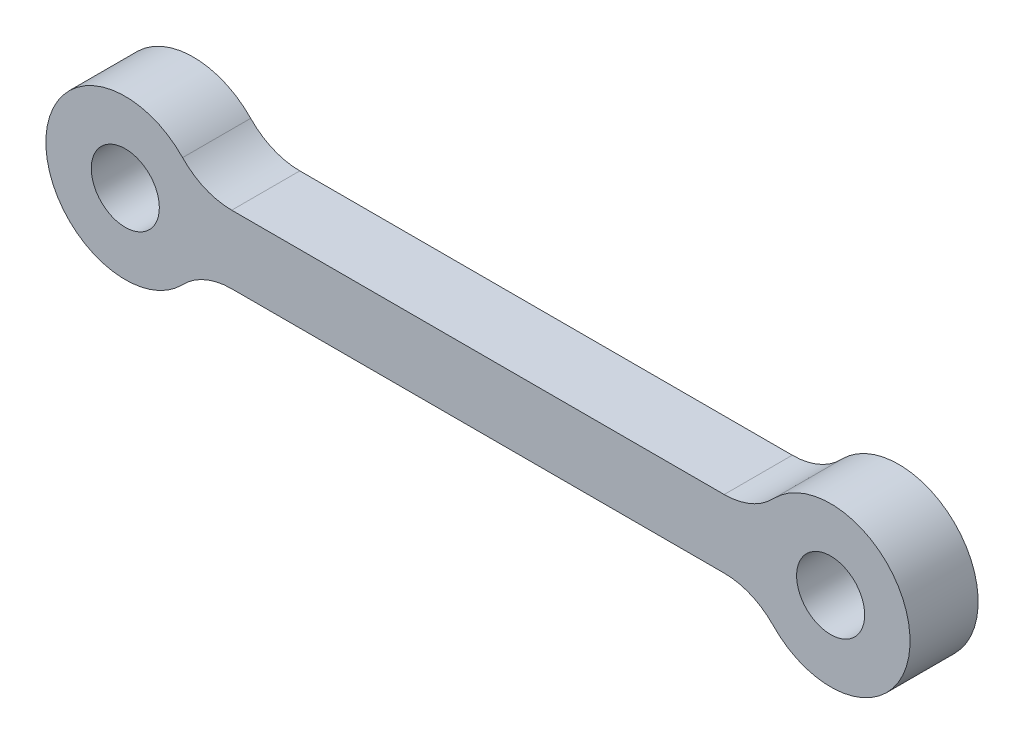
SolidWorks part; units mm, degrees
ref_plane "Front Plane" through (0, 0, 0) normal (0, 0, 1) x (1, 0, 0)
ref_plane "Top Plane" through (0, 0, 0) normal (0, 1, 0) x (1, 0, 0)
ref_plane "Right Plane" through (0, 0, 0) normal (1, 0, 0) x (0, 0, -1)
sketch "Sketch1" plane through (0, 0, 0) normal (0, 0, 1) x (1, 0, 0)
  line L0 (0, 0) -> (31.08, 0) construction
  line L4 (4.6904, 1.5) -> (26.3896, 1.5)
  line L5 (4.6904, -1.5) -> (26.3896, -1.5)
  circle A2 centre (0, 0) radius 1.5
  circle A3 centre (31.08, 0) radius 1.5
  arc A4 (28.5544, -2.4231) -> (28.5544, 2.4231) centre (31.08, 0) ccw
  arc A5 (2.5256, 2.4231) -> (2.5256, -2.4231) centre (0, 0) ccw
  arc A6 (26.3896, -1.5) -> (28.5544, -2.4231) centre (26.3896, -4.5) cw
  arc A7 (26.3896, 1.5) -> (28.5544, 2.4231) centre (26.3896, 4.5) ccw
  arc A8 (4.6904, -1.5) -> (2.5256, -2.4231) centre (4.6904, -4.5) ccw
  arc A9 (4.6904, 1.5) -> (2.5256, 2.4231) centre (4.6904, 4.5) cw
  point P3 (15.54, 0)
  dimension "D3" = 3
  dimension "D6" = 3
  dimension "D1" = 31.08
  dimension "D4" = 3
  dimension "D5" = 1.5
extrude "Boss-Extrude1" add sketch "Sketch1" along normal blind 3
